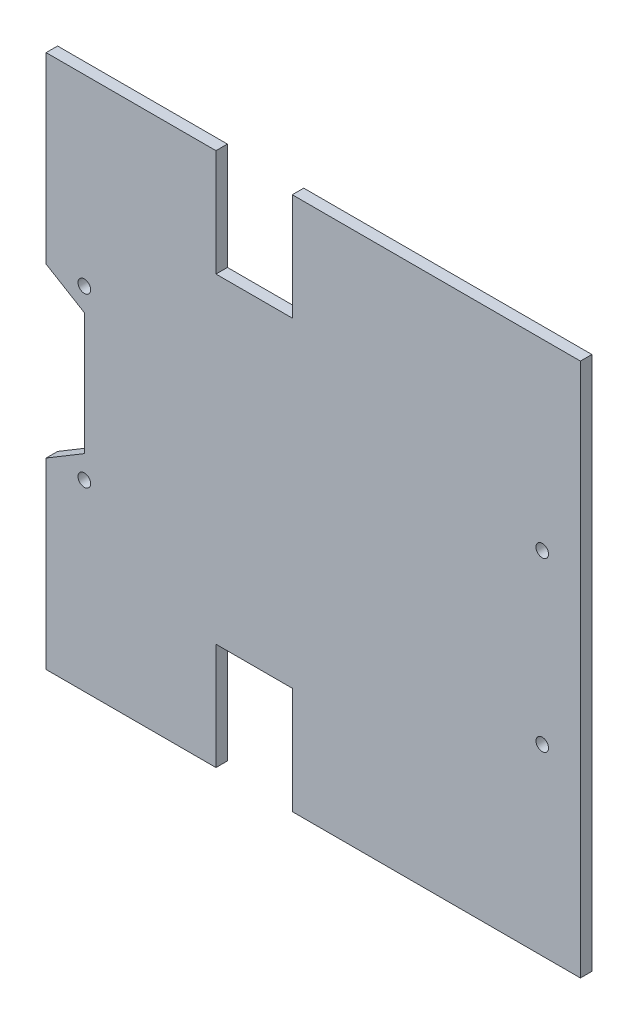
SolidWorks part; units mm, degrees
material "MDF"
ref_plane "Front Plane" through (0, 0, 0) normal (0, 0, 1) x (1, 0, 0)
ref_plane "Top Plane" through (0, 0, 0) normal (0, 1, 0) x (1, 0, 0)
ref_plane "Right Plane" through (0, 0, 0) normal (1, 0, 0) x (0, 0, -1)
sketch "Sketch1" plane through (0, 0, 0) normal (0, 0, 1) x (1, 0, 0)
  line L0 (0, -26) -> (44.5, -26)
  line L1 (140, 114) -> (140, 66)
  line L2 (0, 114) -> (0, 66)
  line L3 (0, 22) -> (0, -26)
  line L4 (0, 114) -> (44.5, 114)
  line L5 (140, 66) -> (140, 22)
  line L7 (140, -26) -> (140, 22)
  line L8 (10, 22) -> (130, 22) construction
  line L9 (130, 44) -> (0, 44) construction
  line L10 (64.5, -26) -> (140, -26)
  line L11 (140, 77.573) -> (0, 77.573) construction
  line L12 (44.5, -26) -> (44.5, 2)
  line L13 (44.5, 2) -> (64.5, 2)
  line L14 (64.5, -26) -> (64.5, 2)
  line L15 (44.5, 86) -> (44.5, 114)
  line L16 (64.5, 86) -> (64.5, 114)
  line L17 (64.5, 86) -> (44.5, 86)
  line L18 (64.5, 114) -> (140, 114)
  line L19 (0, 77.573) -> (70, 77.573) construction
  line L20 (70, 77.573) -> (70, 66) construction
  line L21 (10, 28) -> (0, 22)
  line L22 (10, 60) -> (0, 66)
  line L23 (10, 60) -> (10, 28)
  circle A0 centre (10, 22) radius 1.65
  circle A1 centre (130, 66) radius 1.65
  circle A2 centre (130, 22) radius 1.65
  circle A3 centre (10, 66) radius 1.65
  dimension "D4" = 10
  dimension "D9" = 3.3
  dimension "D1" = 140
  dimension "D2" = 140
  dimension "D3" = 22
  dimension "D5" = 120
  dimension "D6" = 44
  dimension "D10" = 20
  dimension "D12" = 28
  dimension "D13" = 28
extrude "Boss-Extrude1" add sketch "Sketch1" along normal blind 3
